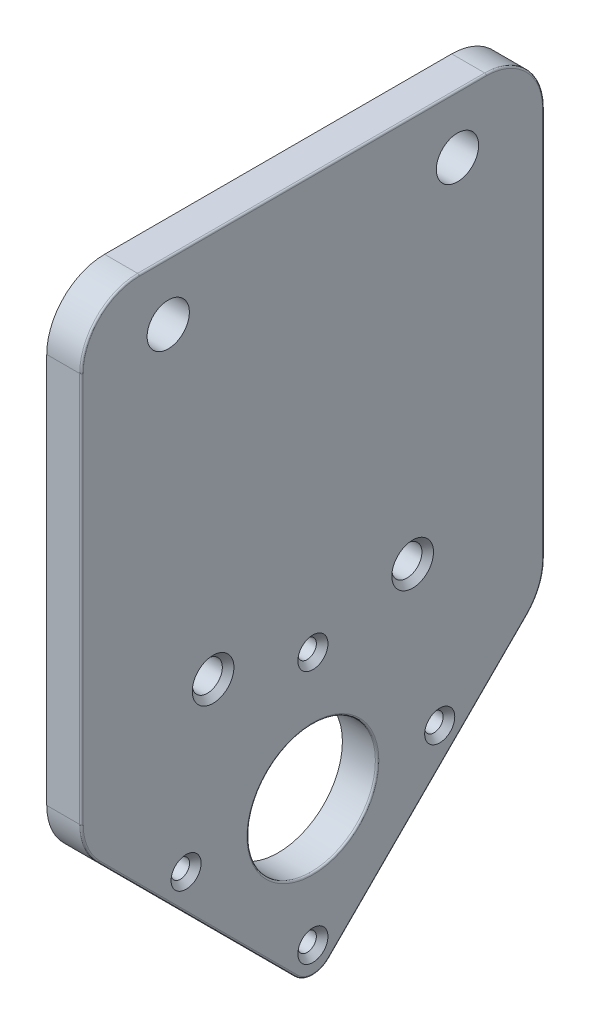
SolidWorks part; units mm, degrees
ref_plane "Спереди (Плоскость XY)" through (0, 0, 0) normal (0, 0, 1) x (1, 0, 0)
ref_plane "Сверху (Плоскость XZ)" through (0, 0, 0) normal (0, 1, 0) x (1, 0, 0)
ref_plane "Справа (Плоскость ZY)" through (0, 0, 0) normal (1, 0, 0) x (0, 0, -1)
sketch "Эскиз2" plane through (0, 0, 0) normal (1, 0, 0) x (0, 0, -1)
  line L0 (-10.5518, -35.8284) -> (10.5656, -56.9458) construction
  line L1 (11.8795, -34.5145) -> (-11.8657, -58.2597) construction
  line L2 (-5.8996, -46.3871) -> (5.818, -46.3871) construction
  line L3 (-30, 47.1129) -> (30, 47.1129)
  line L5 (37.0711, -37.4625) -> (2.8284, -71.7051)
  line L6 (40, 37.1129) -> (40, -30.3914)
  line L141 (-40, 37.1129) -> (-40, -30.3914)
  line L142 (-37.0711, -37.4625) -> (-2.8284, -71.7051)
  circle A1 centre (-21.9134, -46.3871) radius 1.6
  circle A4 centre (17.25, -19.8871) radius 2.6
  circle A5 centre (-17.25, -19.8871) radius 2.6
  circle A6 centre (0.0069, -46.3871) radius 11.1
  circle A7 centre (-25, 37.1129) radius 3.655
  circle A12 centre (25, 37.1129) radius 3.655
  circle A13 centre (0.0069, -24.4668) radius 1.6
  circle A14 centre (21.9272, -46.3871) radius 1.6
  circle A15 centre (0.0069, -68.3074) radius 1.6
  arc A20 (37.0711, -37.4625) -> (40, -30.3914) centre (30, -30.3914) ccw
  arc A21 (-40, -30.3914) -> (-37.0711, -37.4625) centre (-30, -30.3914) ccw
  arc A22 (-2.8284, -71.7051) -> (2.8284, -71.7051) centre (0, -68.8767) ccw
  arc A23 (40, 37.1129) -> (30, 47.1129) centre (30, 37.1129) ccw
  arc A24 (-30, 47.1129) -> (-40, 37.1129) centre (-30, 37.1129) ccw
  point P3 (0, 43.3206)
  point P4 (-25, 37.1129)
  point P5 (-17.25, -19.8871)
  point P7 (17.25, -19.8871)
  point P9 (-21.9134, -46.3871)
  point P11 (0.0069, -46.3871)
  point P12 (25, 37.1129)
  point P43 (0.0069, -46.3871)
  point P63 (40, -34.5335)
  point P66 (-40, -34.5335)
  dimension "D1" = 22.2
  dimension "D2" = 3.2
  dimension "D3" = 5.2
  dimension "D4" = 10
  dimension "D10" = 57
  dimension "D18" = 7.31
  dimension "D19" = 90
  dimension "D20" = 10
  dimension "D15" = 4
  dimension "D5" = 31
  dimension "D6" = 90
  dimension "D7" = 45
  dimension "D8" = 31
  dimension "D11" = 26.5
  dimension "D12" = 10
  dimension "D13" = 34.5
  dimension "D14" = 50
  dimension "D17" = 80
  dimension "D9" = 4
extrude "Бобышка-Вытянуть1" add sketch "Эскиз2" along normal blind 6
fillet "Скругление1" radius 0.3 11 edges at (6, -46.3871, -11.1069) (6, -54.5838, 19.9497) (6, -34.2182, 39.2388) (6, 3.3607, 40) (6, 3.3607, -40) (6, -34.2182, -39.2388) (6, -54.5838, -19.9497) (6, -72.8767, 0) (6, 44.184, 37.0711) (6, 47.1129, 0) (6, 44.184, -37.0711)
chamfer "Фаска1" distance 1 angle 45 6 edges at (6, -68.3074, -1.6069) (6, -46.3871, -23.5272) (6, -46.3871, 20.3134) (6, -24.4668, -1.6069) (6, -19.8871, -19.85) (6, -19.8871, 14.65)
equation "\"deltahole\"= 0.5"
